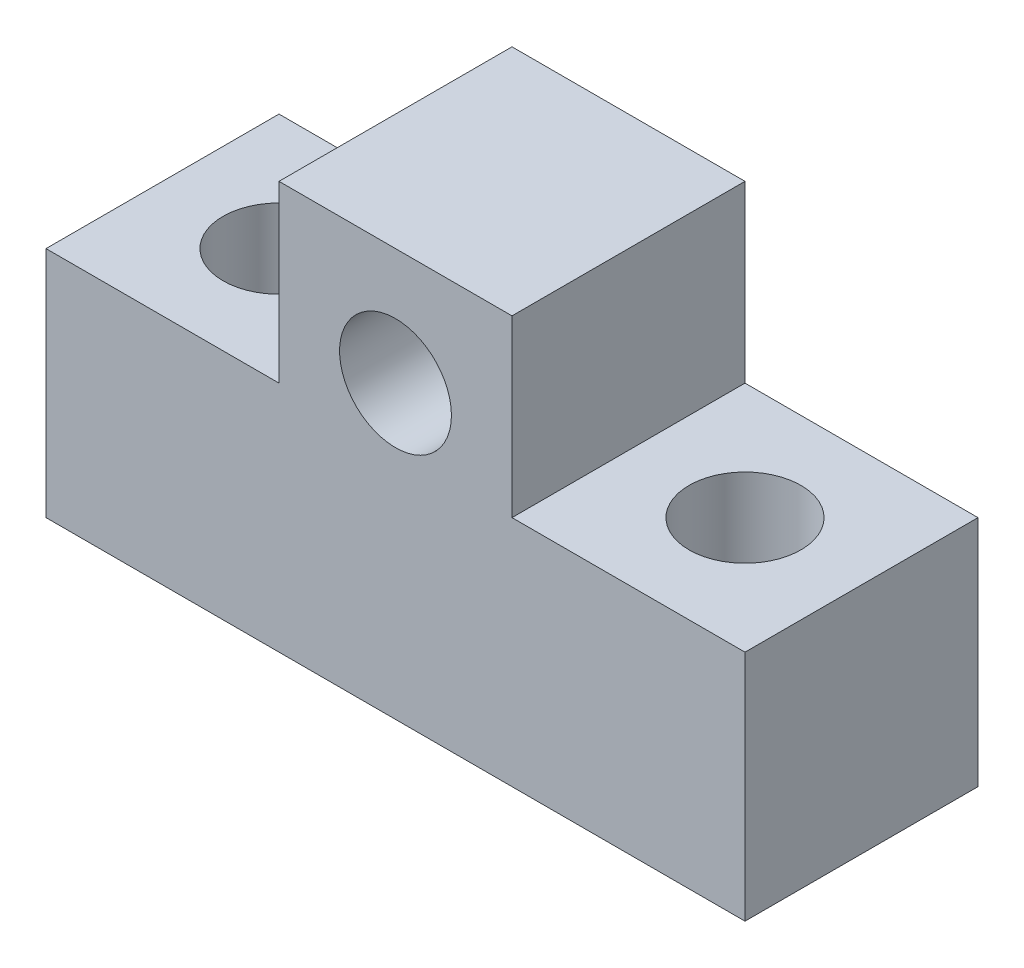
SolidWorks part; units mm, degrees
material "6061-T6 (SS)"
ref_plane "Front Plane" through (0, 0, 0) normal (0, 0, 1) x (1, 0, 0)
ref_plane "Top Plane" through (0, 0, 0) normal (0, 1, 0) x (1, 0, 0)
ref_plane "Right Plane" through (0, 0, 0) normal (1, 0, 0) x (0, 0, -1)
sketch "Sketch1" plane through (0, 0, 0) normal (0, 0, 1) x (1, 0, 0)
  line L0 (-9.525, 3.175) -> (9.525, -3.175) construction
  line L1 (-9.525, 3.175) -> (9.525, 3.175)
  line L2 (-9.525, 3.175) -> (-9.525, -3.175)
  line L3 (-9.525, -3.175) -> (9.525, -3.175)
  line L4 (9.525, 3.175) -> (9.525, -3.175)
  point P4 (0, 0)
  dimension "D1" = 19.05
  dimension "D2" = 6.35
extrude "Boss-Extrude1" add sketch "Sketch1" along normal blind 6.35
sketch "Sketch6" plane through (0, 3.175, 0) normal (0, 1, 0) x (1, 0, 0)
  line L0 (9.525, 0) -> (-9.525, 0) construction
  line L1 (3.175, 0) -> (-3.175, 0)
  line L2 (3.175, 0) -> (3.175, -6.35)
  line L3 (3.175, -6.35) -> (-3.175, -6.35)
  line L4 (-3.175, 0) -> (-3.175, -6.35)
  line L5 (9.525, -6.35) -> (-9.525, -6.35) construction
  point P8 (0, 0)
  point P9 (0, 0)
  dimension "D1" = 6.35
extrude "Boss-Extrude2" add sketch "Sketch6" along normal blind 4.7625
hole_wizard "Tapped Hole for #4-40 Helicoil1" positions "Sketch2" profile "Sketch3" tap size "#4-40" standard "Helicoil® Inch" end condition through all
sketch "Sketch2" plane through (0, 3.175, 0) normal (0, 1, 0) x (1, 0, 0)
  line L0 (0, 0) -> (0, -6.35) construction
  line L4 (-9.525, -6.35) -> (-9.525, 0) construction
  line L5 (-9.525, -6.35) -> (9.525, -6.35) construction
  line L6 (-9.525, 0) -> (9.525, 0) construction
  point P0 (-6.35, -3.175)
  point P13 (6.35, -3.175)
  point P16 (0, -3.175)
  dimension "D1" = 3.175
sketch "Sketch3" plane through (-6.35, 3.175, 3.175) normal (1, 0, 0) x (0, 0, 1)
  line L0 (0, 0) -> (0, 6.35)
  line L1 (0, 6.35) -> (1.524, 6.35)
  line L2 (1.524, 6.35) -> (1.524, 0)
  line L5 (1.524, 0) -> (0, 0)
  line L11 (0, -6.35) -> (0, 107.95) construction
  dimension "Thru Tap Drill Dia." = 3.048
  dimension "Thru Tap Drill Depth" = 6.35
cosmetic thread "Hole Thread1" parameters "D1"=3.556, "D2"=3.7414
cosmetic thread "Hole Thread2" parameters "D1"=3.556, "D2"=3.7414
hole_wizard "Tapped Hole for #4-40 Helicoil2" positions "Sketch4" profile "Sketch5" tap size "#4-40" standard "Helicoil® Inch" end condition through all
sketch "Sketch4" plane through (0, 0, 6.35) normal (0, 0, 1) x (1, 0, 0)
  line L6 (-3.175, 4.7625) -> (0, 4.7625) construction
  line L7 (-3.175, 7.9375) -> (-3.175, 3.175) construction
  line L8 (0, 4.7625) -> (0, 7.9375) construction
  line L9 (-3.175, 7.9375) -> (3.175, 7.9375) construction
  point P0 (0, 4.7625)
sketch "Sketch5" plane through (0, 4.7625, 6.35) normal (1, 0, 0) x (0, -1, 0)
  line L0 (0, 0) -> (0, 6.35)
  line L1 (0, 6.35) -> (1.524, 6.35)
  line L2 (1.524, 6.35) -> (1.524, 0)
  line L5 (1.524, 0) -> (0, 0)
  line L11 (0, -6.35) -> (0, 107.95) construction
  dimension "Thru Tap Drill Dia." = 3.048
  dimension "Thru Tap Drill Depth" = 6.35
cosmetic thread "Hole Thread3" parameters "D1"=3.556, "D2"=3.7414
